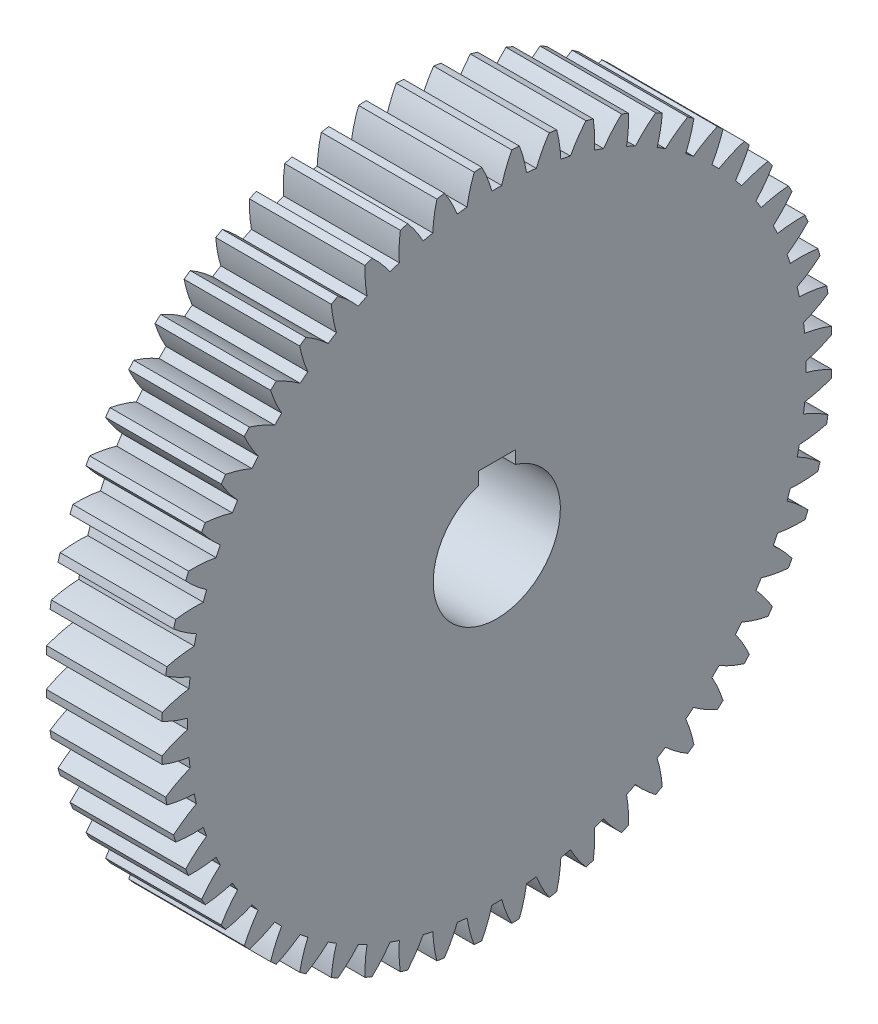
SolidWorks part; units mm, degrees
ref_plane "Plane1" through (0, 0, 0) normal (0, 0, 1) x (1, 0, 0)
ref_plane "Plane2" through (0, 0, 0) normal (0, 1, 0) x (1, 0, 0)
ref_plane "Plane3" through (0, 0, 0) normal (1, 0, 0) x (0, 0, -1)
sketch "HoldingSke" plane through (0, 0, 0) normal (0, 1, 0) x (1, 0, 0)
  line L0 (0, 0) -> (0.1118, -0.1658)
  line L1 (-15, 0) -> (100, 0) construction
  line L2 (0, 0) -> (-2.1039, 2.3779)
  line L3 (0, 0) -> (-11.863, 4.5341)
  line L4 (0, 0) -> (4.8292, 7.1596)
  line L5 (0, 0) -> (-46.8476, -17.4728)
  line L6 (0, 0) -> (-41.4481, -27.9652)
  line L7 (-2.1039, 2.3779) -> (8.6586, 51.2059)
  line L8 (-76.2, 54.61) -> (-71.9, 54.61)
  line L9 (-71.009, 38.7566) -> (-53.1078, 45.2721)
  line L10 (-76.2, 71.12) -> (104.1128, 71.12)
  line L11 (0, 0) -> (-50, 0)
  line L12 (-76.2, 101.6) -> (-76.033, 101.6)
  line L13 (24.9733, 27.94) -> (52.9518, 28.4284)
  line L14 (24.9733, 27.94) -> (24.9743, 27.94)
  line L15 (24.9733, 27.94) -> (100.4006, 29.5858)
  line L16 (-63.627, -5) -> (-12.827, -5)
  circle A0 centre (0, 0) radius 27.5
  circle A1 centre (0, 0) radius 37.5
  circle A2 centre (0, 0) radius 37.5
  circle A3 centre (0, 0) radius 27.5
  dimension "MHD" = 75
  dimension "Hub_dia" = 75
  dimension "Bore" = 55
  dimension "MBD" = 55
  dimension "Num_teeth" = 56
  dimension "Pitch" = 0.2
  dimension "Overall_len" = 50
  dimension "Show_teeth" = 56
  dimension "Thickness" = 50
  dimension "OAL" = 50.0001
  dimension "T_dim" = 4.3
  dimension "Ap" = 20
  dimension "H" = 19.05
  dimension "Pitch_radius" = 180.3128
  dimension "Width" = 50
  dimension "Backlash" = 0.167
  dimension "Addendum_fac" = 1
  dimension "Dedendum_fac" = 1.25
  dimension "Clearance_fac" = 0.25
  dimension "Dedendum_add" = 0.001
  dimension "Module" = 5
sketch "BasProSke" plane through (0, 0, 0) normal (0, 1, 0) x (1, 0, 0)
  line L0 (-10, 0) -> (60, 0) construction
  line L1 (0, 0) -> (0, 145)
  line L2 (0, 0) -> (50, 0)
  line L3 (50, 0) -> (50, 145)
  line L4 (50, 145) -> (0, 145)
  dimension "Thickness" = 50
  dimension "Diameter" = 290
revolve "Base-Revolve" add sketch "BasProSke" angle 360 about L0
sketch "TooCutSke" plane through (0, 0, 0) normal (1, 0, 0) x (0, 0, -1)
  line L1 (0, 0) -> (0, 107) construction
  line L2 (0, 0) -> (-4.2187, 139.9364) construction
  line L3 (0, 0) -> (-15.6944, 279.4653) construction
  line L4 (-4.2187, 139.9364) -> (-7.8472, 139.7327) construction
  arc A0 (2.1269, 133.7321) -> (-2.1269, 133.7321) centre (0, 0) ccw
  arc A1 (6.4996, 144.8797) -> (-6.4996, 144.8797) centre (0, 0) ccw
  circle A2 centre (0, 0) radius 140 construction
  circle A3 centre (0, 0) radius 131.557 construction
  arc A4 (-2.1269, 133.7321) -> (-6.4996, 144.8797) centre (-56.1471, 118.9737) ccw
  arc A5 (6.4996, 144.8797) -> (2.1269, 133.7321) centre (56.1471, 118.9737) ccw
  dimension "Root_dia" = 267.498
  dimension "Overcut_dia" = 290.0508
  dimension "Pitch_dia" = 280
  dimension "Base_dia" = 263.1139
  dimension "Flank_rad" = 56
  dimension "Half_ang" = 3.214
  dimension "Half_CT" = 3.6342
extrude "ToothCut" cut sketch "TooCutSke" along normal through all
fillet "Breaks" [suppressed] radius 0.1
fillet "RootFillets" [suppressed] radius 1.251
pattern_circular "TeethCuts" count 56 every 6.429 about axis through (-10, 0, 0) along (1, 0, 0) of "ToothCut", "RootFillets", "Breaks"
sketch "HubNeaOneSke" plane through (0, 0, 0) normal (-1, 0, 0) x (0, 0, 1)
  circle A0 centre (0, 0) radius 37.5
  dimension "Diameter" = 75
extrude "HubNearOne" [suppressed] add sketch "HubNeaOneSke" along normal blind 12.7001
sketch "HubNeaBotSke" plane through (0, 0, 0) normal (-1, 0, 0) x (0, 0, 1)
  circle A0 centre (0, 0) radius 37.5
  dimension "Diameter" = 75
extrude "HubNearBoth" [suppressed] add sketch "HubNeaBotSke" along normal blind 6.35
ref_plane "FarPln" through (50, 0, 0) normal (1, 0, 0) x (0, 0, -1)
sketch "HubFarSke" plane through (50, 0, 0) normal (1, 0, 0) x (0, 0, -1)
  circle A0 centre (0, 0) radius 37.5
  dimension "Diameter" = 75
extrude "HubFar" [suppressed] add sketch "HubFarSke" along normal blind 6.35
sketch "BorSke" plane through (0, 0, 0) normal (1, 0, 0) x (0, 0, -1)
  circle A0 centre (0, 0) radius 27.5
  dimension "Diameter" = 55
extrude "Bore" cut sketch "BorSke" along normal mid plane 100.0001
sketch "KeySke" plane through (0, 0, 0) normal (1, 0, 0) x (0, 0, -1)
  line L0 (-8, 0) -> (-8, 31.8)
  line L1 (-8, 31.8) -> (8, 31.8)
  line L2 (8, 31.8) -> (8, 0)
  line L3 (0, 0) -> (0, 34) construction
  line L4 (-8, 0) -> (8, 0)
  dimension "Offset" = 31.8
  dimension "Width" = 16
extrude "Keyway" cut sketch "KeySke" along normal mid plane 100.0001
pattern_circular "Keyway2" [suppressed] count 2 every 90 about axis through (-10, 0, 0) along (1, 0, 0)
equation "' \"Module@HoldingSke\" = 6.35"
equation "' \"Num_teeth@HoldingSke\" = 12"
equation "' \"Ap@HoldingSke\" =  20"
equation "' \"Ap@HoldingSke\" = 20"
equation "' \"Width@HoldingSke\" = 0.5 * 25.4"
equation "' \"Hub_dia@HoldingSke\"= 1 * 25.4"
equation "' \"Hub_dia@HoldingSke\" = 1 * 25.4"
equation "' \"Overall_len@HoldingSke\" = 1.0 * 25.4"
equation "' \"Bore@HoldingSke\" = 0.75 * 25.4"
equation "' \"T_dim@HoldingSke\" = 0.1 * 25.4"
equation "' \"Width@KeySke\" = 0.25 * 25.4"
equation "' \"Show_teeth@HoldingSke\" = 13"
equation "' \"Backlash@HoldingSke\" = 0.009 * 25.4"
equation "' \"Addendum_fac@HoldingSke\" = 1.0"
equation "' \"Dedendum_fac@HoldingSke\" = 1.25"
equation "' \"Dedendum_add@HoldingSke\" = 0.00005 * 25.4"
equation "' \"Clearance_fac@HoldingSke\" = 0.25"
equation "\"Pitch@HoldingSke\" = 1 / \"Module@HoldingSke\""
equation "\"Overcut_dia@TooCutSke\" = (\"Num_teeth@HoldingSke\" + 2 * \"Addendum_fac@HoldingSke\") / \"Pitch@HoldingSke\" + 0.002 * 25.4"
equation "\"Pitch_dia@TooCutSke\" = \"Num_teeth@HoldingSke\" / \"Pitch@HoldingSke\""
equation "\"Base_dia@TooCutSke\" = \"Num_teeth@HoldingSke\" / \"Pitch@HoldingSke\" * cos((\"Ap@HoldingSke\"  * 3.14159265 / 180))"
equation "\"Root_dia@TooCutSke\" = (\"Num_teeth@HoldingSke\" + 2) / \"Pitch@HoldingSke\" - 2 * (\"Addendum_fac@HoldingSke\" + \"Dedendum_fac@HoldingSke\") / \"Pitch@HoldingSke\" - \"Dedendum_add@HoldingSke\" * 2"
equation "\"Half_ang@TooCutSke\" = 180 / \"Num_teeth@HoldingSke\""
equation "\"Half_CT@TooCutSke\" = \"Num_teeth@HoldingSke\" / \"Pitch@HoldingSke\" * sin((3.14159265 / 2 / \"Num_teeth@HoldingSke\")) / 2 - 7 * \"Backlash@HoldingSke\" / 4"
equation "\"Flank_rad@TooCutSke\" = \"Num_teeth@HoldingSke\" / \"Pitch@HoldingSke\" / 5"
equation "\"Radius@RootFillets\" = \"Clearance_fac@HoldingSke\" / \"Pitch@HoldingSke\" + \"Dedendum_add@HoldingSke\""
equation "\"Break_rad@Breaks\" = 0.02 / \"Pitch@HoldingSke\""
equation "\"Thickness@HoldingSke\" = \"Width@HoldingSke\""
equation "\"OAL@HoldingSke\" = \"Thickness@HoldingSke\""
equation "\"MHD@HoldingSke\" = (\"Num_teeth@HoldingSke\" + 2) / \"Pitch@HoldingSke\" - 2 * (\"Addendum_fac@HoldingSke\" + \"Dedendum_fac@HoldingSke\")  / \"Pitch@HoldingSke\" - \"Dedendum_add@HoldingSke\" * 2"
equation "\"MBD@HoldingSke\" = (\"Num_teeth@HoldingSke\" + 2) / \"Pitch@HoldingSke\" - 2 * (\"Addendum_fac@HoldingSke\" + \"Dedendum_fac@HoldingSke\")  / \"Pitch@HoldingSke\" - \"Dedendum_add@HoldingSke\" * 2 - 0.002 * 25.4"
equation "\"MHD@HoldingSke\" = ((sgn( \"MHD@HoldingSke\" - \"Hub_dia@HoldingSke\" )-1)*( \"MHD@HoldingSke\" - \"Hub_dia@HoldingSke\" ))/-2+ \"Hub_dia@HoldingSke\""
equation "\"MBD@HoldingSke\" = ((sgn( \"MBD@HoldingSke\" - \"Bore@HoldingSke\" )-1)*( \"MBD@HoldingSke\" - \"Bore@HoldingSke\" ))/-2+ \"Bore@HoldingSke\""
equation "\"OAL@HoldingSke\" = ((sgn( \"OAL@HoldingSke\" - \"Overall_len@HoldingSke\" )+1)*( \"OAL@HoldingSke\" - \"Overall_len@HoldingSke\" ))/2 + \"Overall_len@HoldingSke\" + 0.000002 * 25.4"
equation "\"Num_teeth@TeethCuts\" = int( \"Show_teeth@HoldingSke\" ) + 1"
equation "\"Num_teeth@TeethCuts\" = ((sgn( \"Num_teeth@TeethCuts\" - \"Num_teeth@HoldingSke\" )-1)*( \"Num_teeth@TeethCuts\" - \"Num_teeth@HoldingSke\" ))/-2+ \"Num_teeth@HoldingSke\""
equation "\"Num_teeth@TeethCuts\" = ((sgn( \"Num_teeth@TeethCuts\" - 2.0)+1)*( \"Num_teeth@TeethCuts\" - 2.0))/2 +2.0"
equation "\"Angle@TeethCuts\" = 360.0 / \"Num_teeth@HoldingSke\""
equation "\"Diameter@BasProSke\" = (\"Num_teeth@HoldingSke\" + 2 * \"Addendum_fac@HoldingSke\") / \"Pitch@HoldingSke\""
equation "\"Thickness@BasProSke\"  = \"Thickness@HoldingSke\""
equation "' \"Fillet_rad@BasProSke\" =  \"Thickness@HoldingSke\" * 0.05"
equation "' \"Fillet_rad@BasProSke\" = \"Thickness@HoldingSke\" * 0.05"
equation "\"MHD@HoldingSke\" = ((sgn( \"MHD@HoldingSke\" - \"Root_dia@TooCutSke\" )-1)*( \"MHD@HoldingSke\" - \"Root_dia@TooCutSke\" ))/-2+ \"Root_dia@TooCutSke\""
equation "\"Diameter@HubNeaOneSke\" = \"MHD@HoldingSke\""
equation "\"Length@HubNearOne\" = \"OAL@HoldingSke\" - \"Thickness@BasProSke\""
equation "\"Diameter@HubNeaBotSke\" = \"MHD@HoldingSke\""
equation "\"Length@HubNearBoth\" = ( \"OAL@HoldingSke\" - \"Thickness@BasProSke\" ) / 2.0"
equation "\"Thickness@FarPln\" = \"Thickness@BasProSke\""
equation "\"Diameter@HubFarSke\" = \"MHD@HoldingSke\""
equation "\"Length@HubFar\" = ( \"OAL@HoldingSke\" - \"Thickness@BasProSke\" ) / 2.0"
equation "\"Diameter@BorSke\" = \"MBD@HoldingSke\""
equation "\"D1@Bore\" = \"OAL@HoldingSke\" * 2.0"
equation "\"D1@Keyway\" = \"OAL@HoldingSke\" * 2.0"
equation "\"Offset@KeySke\" = \"T_dim@HoldingSke\" + \"MBD@HoldingSke\" / 2.0"
